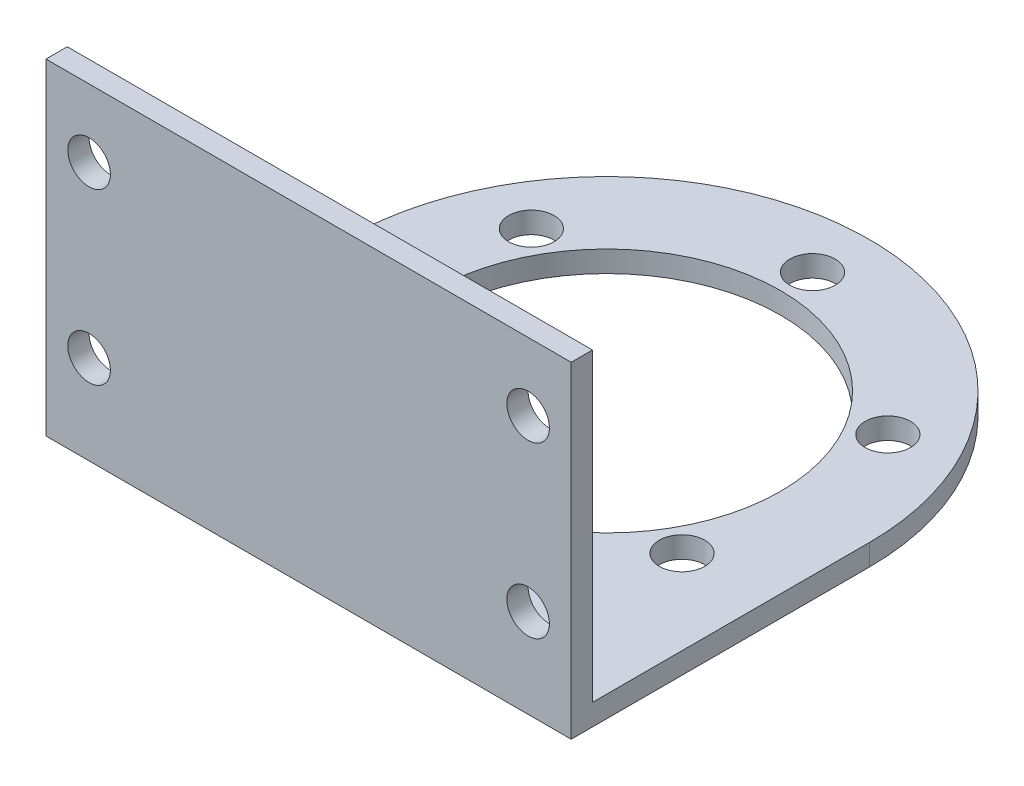
SolidWorks part; units mm, degrees
ref_plane "Front Plane" through (0, 0, 0) normal (0, 0, 1) x (1, 0, 0)
ref_plane "Top Plane" through (0, 0, 0) normal (0, 1, 0) x (1, 0, 0)
ref_plane "Right Plane" through (0, 0, 0) normal (1, 0, 0) x (0, 0, -1)
sketch "Sketch1" plane through (0, 0, 0) normal (0, 1, 0) x (1, 0, 0)
  line L2 (-23.3913, 9.0622) -> (-23.3913, -11.9378)
  line L3 (-23.3913, -11.9378) -> (13.6087, -11.9378)
  line L4 (13.6087, 9.0622) -> (13.6087, -11.9378)
  arc A0 (13.6087, 9.0622) -> (-23.3913, 9.0622) centre (-4.8913, 9.0622) ccw
  circle A1 centre (-4.8913, 9.0622) radius 12.25
  dimension "D1" = 37
  dimension "D2" = 24.5
  dimension "D3" = 21
extrude "Boss-Extrude1" add sketch "Sketch1" along normal blind 1.5
sketch "Sketch3" plane through (0, 1.5, 0) normal (0, 1, 0) x (1, 0, 0)
  circle A1 centre (-4.8913, 23.5622) radius 1.6
  dimension "D1" = 3.2
  dimension "D2" = 14.5
sketch "Sketch4" plane through (0, 1.5, 0) normal (0, 1, 0) x (1, 0, 0)
  line L0 (13.6087, -11.9378) -> (13.6087, 9.0622) construction
  line L1 (-23.3913, -11.9378) -> (13.6087, -11.9378)
  line L2 (-23.3913, -11.9378) -> (-23.3913, -10.4378)
  line L3 (-23.3913, -10.4378) -> (13.6087, -10.4378)
  line L4 (13.6087, -11.9378) -> (13.6087, -10.4378)
  dimension "D1" = 1.5
extrude "Boss-Extrude2" add sketch "Sketch4" along normal blind 21.5
sketch "Sketch6" plane through (0, 0, 10.4378) normal (0, 0, -1) x (-1, 0, 0)
  line L0 (4.8913, 1.5) -> (4.8913, 23)
  line L1 (-13.6087, 1.5) -> (23.3913, 1.5) construction
  line L2 (-13.6087, 23) -> (23.3913, 23) construction
  line L3 (23.3913, 12.25) -> (-13.6087, 12.25)
  line L4 (23.3913, 23) -> (23.3913, 1.5) construction
  line L5 (-13.6087, 23) -> (-13.6087, 1.5) construction
  circle A0 centre (-10.5735, 6.2796) radius 1.5
  circle A1 centre (20.3561, 6.2796) radius 1.5
  circle A2 centre (20.3561, 18.2204) radius 1.5
  circle A3 centre (-10.5735, 18.2204) radius 1.5
  dimension "D1" = 3
extrude "Cut-Extrude2" cut sketch "Sketch6" against normal blind 10 contours A0 | A1 | A2 | A3
extrude "Cut-Extrude3" cut sketch "Sketch3" against normal blind 10
pattern_circular "CirPattern1" count 6 over 360 about axis through (-4.8913, 0, -9.0622) along (0, 1, 0) of "Cut-Extrude3"
